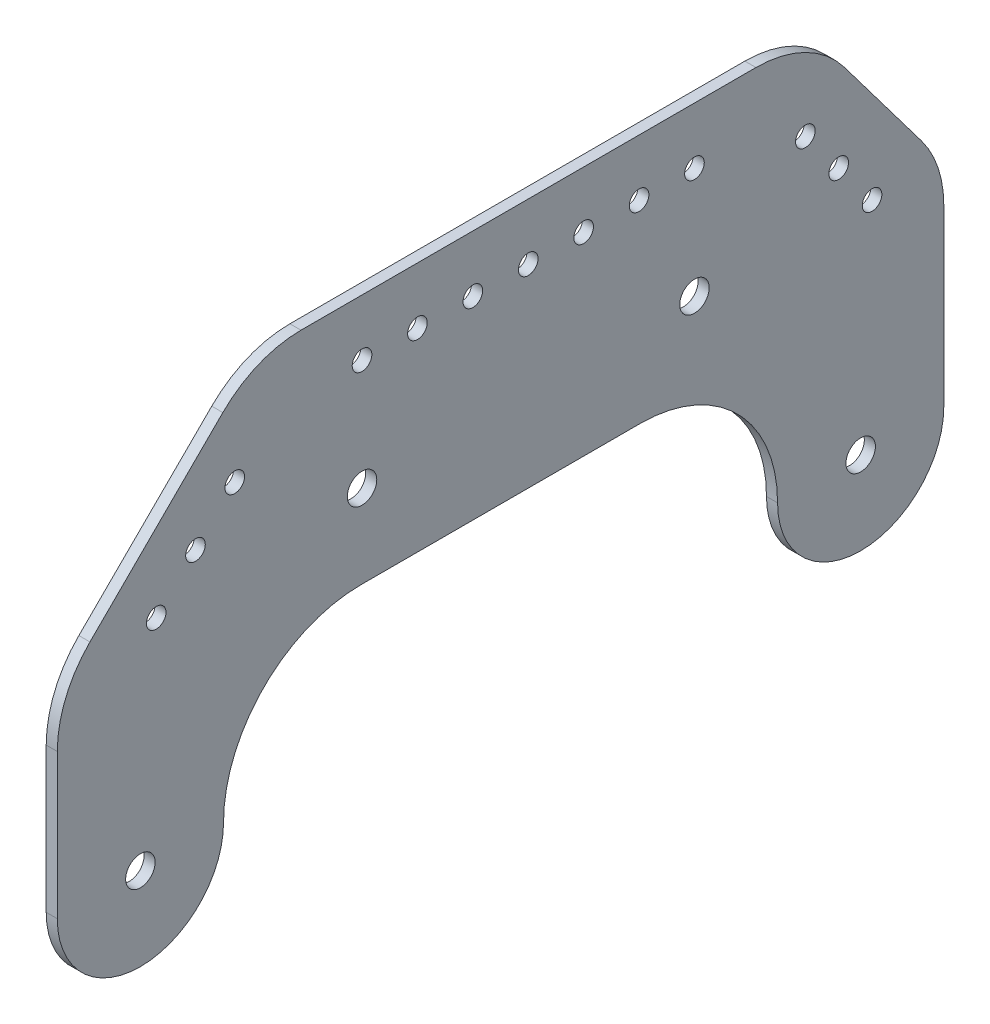
SolidWorks part; units mm, degrees
ref_plane "Front" through (0, 0, 0) normal (0, 0, 1) x (1, 0, 0)
ref_plane "Top" through (0, 0, 0) normal (0, 1, 0) x (1, 0, 0)
ref_plane "Right" through (0, 0, 0) normal (1, 0, 0) x (0, 0, -1)
sketch "Sketch1" plane through (0, 0, 0) normal (1, 0, 0) x (0, 0, -1)
  line L0 (-13.4366, 13.5041) -> (37.3634, 64.0501) construction
  line L1 (50.8, 69.596) -> (127, 69.596) construction
  line L2 (142.2124, 62.0127) -> (180.3124, 11.4667) construction
  line L3 (50.546, 31.496) -> (114.554, 31.496)
  line L4 (-19.05, 0) -> (-19.05, 33.1918)
  line L5 (36.8106, 88.9) -> (141.0913, 88.9)
  line L6 (184.15, 40.0728) -> (184.15, 0)
  line L7 (-11.5654, 51.1972) -> (18.8951, 81.5055)
  line L8 (161.3746, 78.7889) -> (179.0332, 55.3617)
  arc A4 (-19.05, 0) -> (19.05, 0) centre (0, 0) ccw
  arc A5 (50.8, 69.596) -> (37.3634, 64.0501) centre (50.8, 50.546) ccw construction
  arc A6 (142.2124, 62.0127) -> (127, 69.596) centre (127, 50.546) ccw construction
  arc A7 (146.05, 0) -> (184.15, 0) centre (165.1, 0) ccw
  circle A8 centre (165.1, 0) radius 16.8275 construction
  circle A9 centre (127, 50.546) radius 16.8275 construction
  circle A10 centre (50.8, 50.546) radius 16.8275 construction
  arc A11 (50.546, 31.496) -> (19.05, 0) centre (50.546, 0) ccw
  arc A12 (146.05, 0) -> (114.554, 31.496) centre (114.554, 0) ccw
  arc A13 (179.0332, 55.3617) -> (184.15, 40.0728) centre (158.75, 40.0728) cw
  arc A14 (161.3746, 78.7889) -> (141.0913, 88.9) centre (141.0913, 63.5) ccw
  arc A15 (18.8951, 81.5055) -> (36.8106, 88.9) centre (36.8106, 63.5) cw
  arc A16 (-11.5654, 51.1972) -> (-19.05, 33.1918) centre (6.35, 33.1918) ccw
  dimension "D1" = 38.1
  dimension "D5" = 25.4
  dimension "D2" = 88.9
  dimension "D3" = 25.4
  dimension "D4" = 25.4
extrude "Boss-Extrude1" add sketch "Sketch1" along normal blind 2.54 contours A4 A11 L3 A12 A7 L6 A13 L8 A14 L5 A15 L7 A16 L4
hole_wizard "1/4 Clearance Hole1" positions "Sketch2" profile "Sketch3" hole size "1/4" standard "ANSI Inch" end condition through all
sketch "Sketch2" plane through (2.54, 0, 0) normal (1, 0, 0) x (0, 0, -1)
  arc A2 (146.05, 0) -> (184.15, 0) centre (165.1, 0) ccw construction
  circle A3 centre (50.8, 50.546) radius 17.4625 construction
  circle A4 centre (127, 50.546) radius 17.4625 construction
  point P0 (50.8, 50.546)
  point P2 (127, 50.546)
  point P4 (165.1, 0)
  point P6 (0, 0)
sketch "Sketch3" plane through (2.54, 50.546, -50.8) normal (0, 1, 0) x (0, 0, -1)
  line L0 (0, 0) -> (0, 2.54)
  line L1 (0, 2.54) -> (3.3782, 2.54)
  line L2 (3.3782, 2.54) -> (3.3782, 0)
  line L5 (3.3782, 0) -> (0, 0)
  line L11 (0, -6.35) -> (0, 107.95) construction
  dimension "Thru Hole Dia." = 6.7564
  dimension "Thru Hole Depth" = 2.54
hole_wizard "#8 Clearance Hole2" positions "Sketch5" profile "Sketch4" hole size "#8" standard "ANSI Inch"
sketch "Sketch5" plane through (2.54, 0, 0) normal (1, 0, 0) x (0, 0, -1)
  line L4 (167.7067, 49.2892) -> (152.4178, 69.5725)
  line L6 (3.6198, 48.3909) -> (12.6226, 57.3486) construction
  line L7 (12.6226, 57.3486) -> (21.6253, 66.3063) construction
  line L13 (0, 0) -> (50.8, 50.546) construction
  line L14 (76.2, 75.946) -> (88.9, 75.946)
  line L15 (88.9, 75.946) -> (101.6, 75.946)
  line L19 (127, 50.546) -> (165.1, 0) construction
  line L24 (160.0623, 59.4309) -> (170.2039, 67.0753)
  line L25 (161.3746, 78.7889) -> (179.0332, 55.3617) construction
  line L27 (50.8, 50.546) -> (127, 50.546) construction
  line L29 (88.9, 75.946) -> (88.9, 50.546) construction
  line L31 (76.2, 75.946) -> (63.5, 75.946)
  line L32 (63.5, 75.946) -> (50.8, 75.946)
  line L35 (101.6, 75.946) -> (114.3, 75.946)
  line L36 (114.3, 75.946) -> (127, 75.946)
  line L38 (3.6648, 66.3513) -> (12.6226, 57.3486) construction
  line L39 (-11.5654, 51.1972) -> (18.8951, 81.5055) construction
  point P1 (76.2, 75.946)
  point P3 (88.9, 75.946)
  point P5 (101.6, 75.946)
  point P7 (21.6253, 66.3063)
  point P9 (12.6226, 57.3486)
  point P11 (3.6198, 48.3909)
  point P13 (152.4178, 69.5725)
  point P15 (160.0623, 59.4309)
  point P17 (167.7067, 49.2892)
  point P130 (63.5, 75.946)
  point P133 (50.8, 75.946)
  point P136 (114.3, 75.946)
  point P139 (127, 75.946)
  dimension "D5" = 25.4
  dimension "D1" = 31.75
  dimension "D2" = 12.7
  dimension "D3" = 25.4
  dimension "D4" = 31.75
sketch "Sketch4" plane through (2.54, 75.946, -76.2) normal (0, 1, 0) x (0, 0, -1)
  line L0 (0, 0) -> (0, 3.8897)
  line L1 (0, 3.8897) -> (2.2479, 2.539)
  line L2 (2.2479, 2.539) -> (2.2479, 0)
  line L5 (2.2479, 0) -> (0, 0)
  line L10 (0, 3.8897) -> (-2.2479, 2.539) construction
  line L11 (0, -6.35) -> (0, 107.95) construction
  dimension "Hole Dia." = 4.4958
  dimension "Hole Depth" = 2.539
  dimension "Drill Angle" = 118
